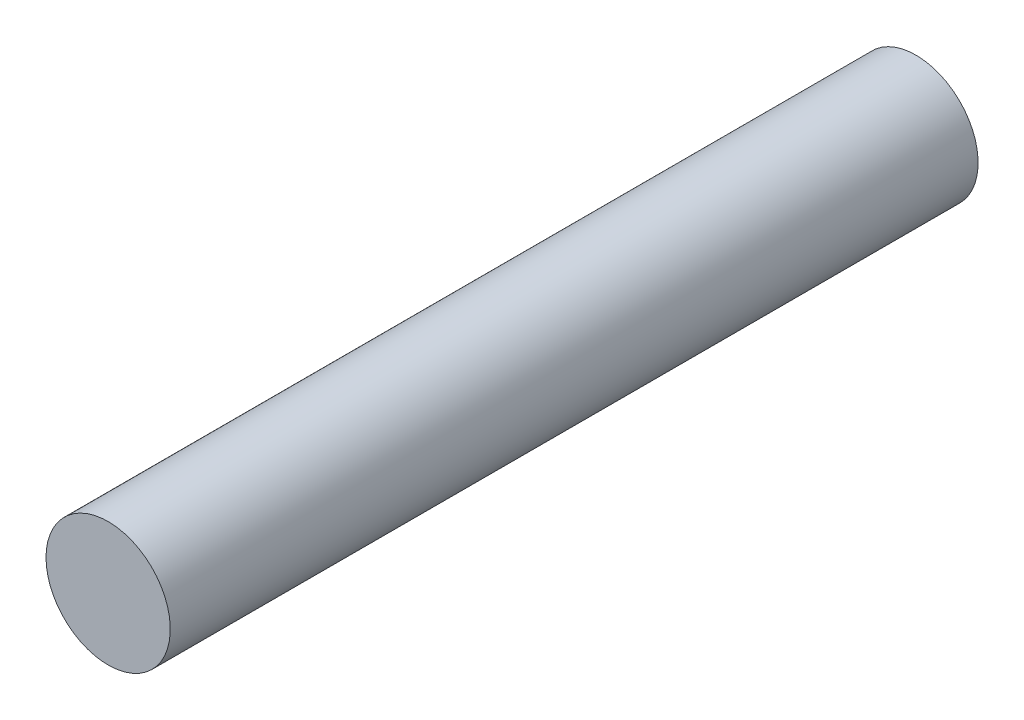
SolidWorks part; units mm, degrees
ref_plane "Alzado" through (0, 0, 0) normal (0, 0, 1) x (1, 0, 0)
ref_plane "Planta" through (0, 0, 0) normal (0, 1, 0) x (1, 0, 0)
ref_plane "Vista lateral" through (0, 0, 0) normal (1, 0, 0) x (0, 0, -1)
sketch "Croquis1" plane through (0, 0, 0) normal (0, 0, 1) x (1, 0, 0)
  circle A0 centre (0, 0) radius 2
  dimension "D1" = 4
extrude "Saliente-Extruir1" add sketch "Croquis1" along normal blind 26
